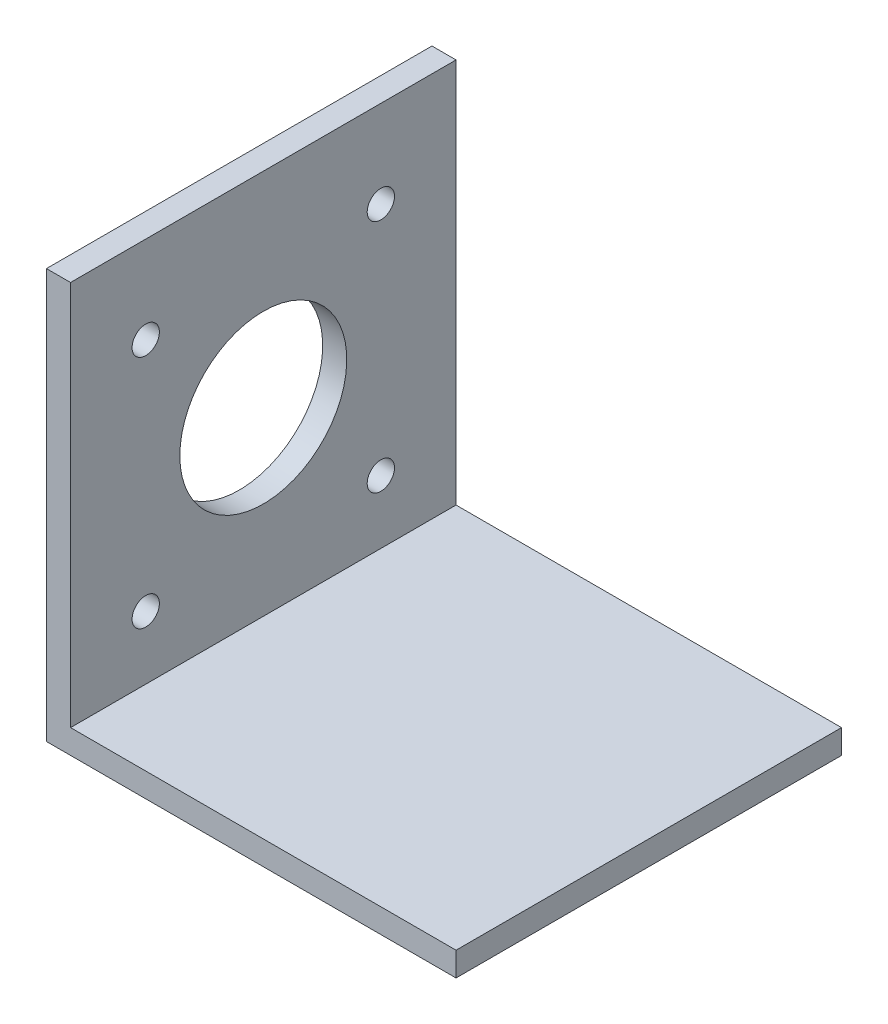
SolidWorks part; units mm, degrees
ref_plane "Front Plane" through (0, 0, 0) normal (0, 0, 1) x (1, 0, 0)
ref_plane "Top Plane" through (0, 0, 0) normal (0, 1, 0) x (1, 0, 0)
ref_plane "Right Plane" through (0, 0, 0) normal (1, 0, 0) x (0, 0, -1)
sketch "Sketch1" plane through (0, 0, 0) normal (0, 0, 1) x (1, 0, 0)
  line L0 (0, 50.8) -> (0, 0)
  line L1 (0, 0) -> (50.8, 0)
  dimension "D1" = 50.8
  dimension "D2" = 50.8
extrude "Extrude-Thin1" add sketch "Sketch1" along normal blind 50.8 thin
sketch "Sketch2" plane through (-3.175, 0, 0) normal (-1, 0, 0) x (0, 0, 1)
  line L0 (25.4, 50.8) -> (25.4, -3.175) construction
  line L1 (50.8, 50.8) -> (0, 50.8) construction
  line L2 (50.8, -3.175) -> (0, -3.175) construction
  circle A0 centre (25.4, 23.8125) radius 11
  dimension "D1" = 22
extrude "Cut-Extrude1" cut sketch "Sketch2" against normal through all
hole_wizard "M3 Clearance Hole1" positions "Sketch3" profile "Sketch4" hole size "M3" standard "ANSI Metric" end condition through all
sketch "Sketch3" plane through (-3.175, 0, 0) normal (-1, 0, 0) x (0, 0, 1)
  circle A0 centre (25.4, 23.8125) radius 21.9075 construction
  point P0 (9.9091, 39.3034)
  point P12 (40.8909, 39.3034)
  point P13 (40.8909, 8.3216)
  point P14 (9.9091, 8.3216)
  dimension "D1" = 4
  dimension "D2" = 43.815
sketch "Sketch4" plane through (-3.175, 39.3034, 9.9091) normal (0, 1, 0) x (0, 0, 1)
  line L0 (0, 0) -> (0, 53.975)
  line L1 (0, 53.975) -> (1.8, 53.975)
  line L2 (1.8, 53.975) -> (1.8, 0)
  line L5 (1.8, 0) -> (0, 0)
  line L11 (0, -6.35) -> (0, 107.95) construction
  dimension "Thru Hole Dia." = 3.6
  dimension "Thru Hole Depth" = 53.975
